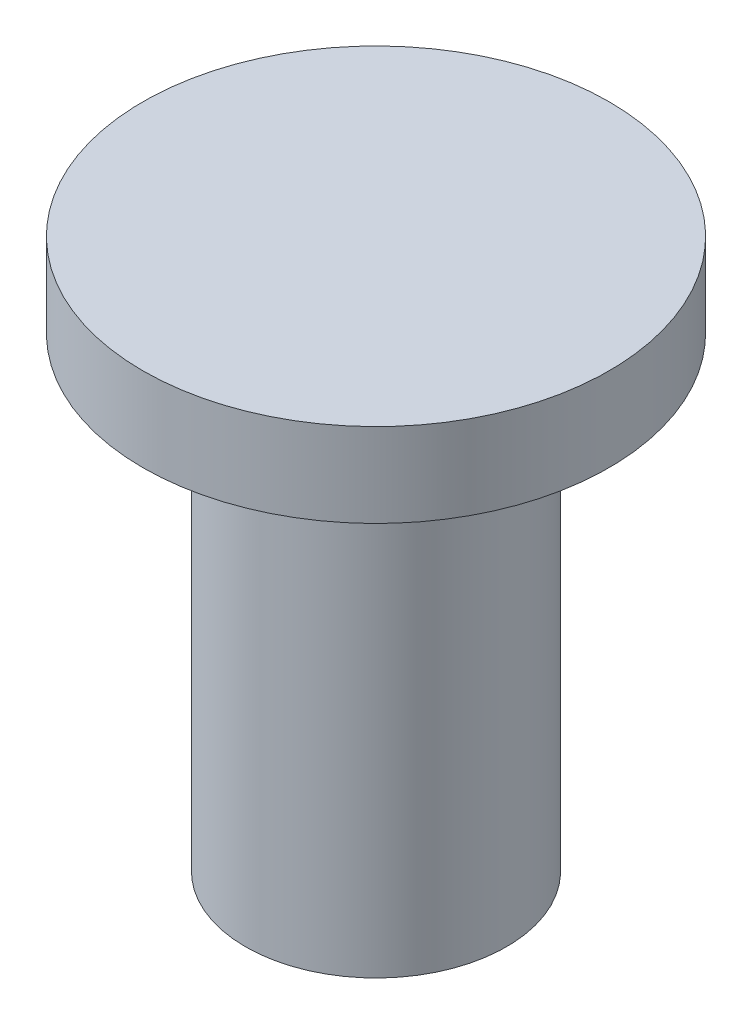
SolidWorks part; units mm, degrees
ref_plane "Front Plane" through (0, 0, 0) normal (0, 0, 1) x (1, 0, 0)
ref_plane "Top Plane" through (0, 0, 0) normal (0, 1, 0) x (1, 0, 0)
ref_plane "Right Plane" through (0, 0, 0) normal (1, 0, 0) x (0, 0, -1)
sketch "Sketch1" plane through (0, 0, 0) normal (0, 1, 0) x (1, 0, 0)
  circle A0 centre (0, 0) radius 1.4
  dimension "D1" = 2.8
extrude "Boss-Extrude1" add sketch "Sketch1" along normal mid plane 5
sketch "Sketch2" plane through (0, 2.5, 0) normal (0, 1, 0) x (1, 0, 0)
  circle A0 centre (0, 0) radius 2.5
  dimension "D1" = 5
extrude "Boss-Extrude2" add sketch "Sketch2" along normal blind 0.9
